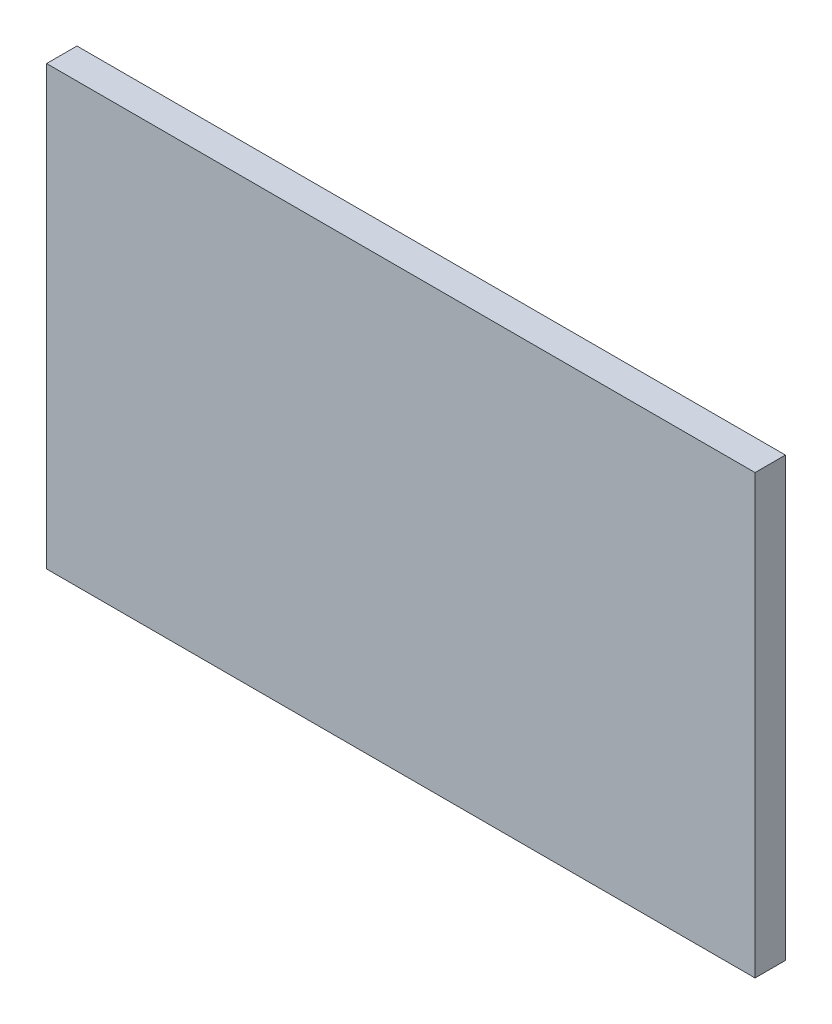
SolidWorks part; units mm, degrees
ref_plane "Front Plane" through (0, 0, 0) normal (0, 0, 1) x (1, 0, 0)
ref_plane "Top Plane" through (0, 0, 0) normal (0, 1, 0) x (1, 0, 0)
ref_plane "Right Plane" through (0, 0, 0) normal (1, 0, 0) x (0, 0, -1)
ref_plane "PZ_m3_17" through (0, 0, -3.17) normal (0, 0, 1) x (1, 0, 0)
sketch "PCB_Sk1" plane through (0, 0, -3.17) normal (0, 0, 1) x (1, 0, 0)
  line L0 (-47.2, -27.2) -> (-19.2, -27.2)
  line L1 (-19.2, -27.2) -> (-19.2, -9.9)
  line L2 (-19.2, -9.9) -> (-47.2, -9.9)
  line L3 (-47.2, -9.9) -> (-47.2, -27.2)
extrude "PCB" add sketch "PCB_Sk1" against normal blind 1.2
ref_plane "PZ_m4_37" through (0, 0, -4.37) normal (0, 0, 1) x (1, 0, 0)
sketch "USB_C_Sk2" plane through (0, 0, -4.37) normal (0, 0, 1) x (1, 0, 0)
  line L0 (-48, -23.02) -> (-40.65, -23.02)
  line L1 (-40.65, -23.02) -> (-40.65, -14.08)
  line L2 (-40.65, -14.08) -> (-48, -14.08)
  line L3 (-48, -14.08) -> (-48, -23.02)
extrude "USB_C" add sketch "USB_C_Sk2" against normal blind 3.26
sketch "Chip_Sk3" plane through (0, 0, -4.37) normal (0, 0, 1) x (1, 0, 0)
  line L0 (-36.2, -21.05) -> (-31.2, -21.05)
  line L1 (-31.2, -21.05) -> (-31.2, -16.05)
  line L2 (-31.2, -16.05) -> (-36.2, -16.05)
  line L3 (-36.2, -16.05) -> (-36.2, -21.05)
extrude "Chip" add sketch "Chip_Sk3" against normal blind 1.6
